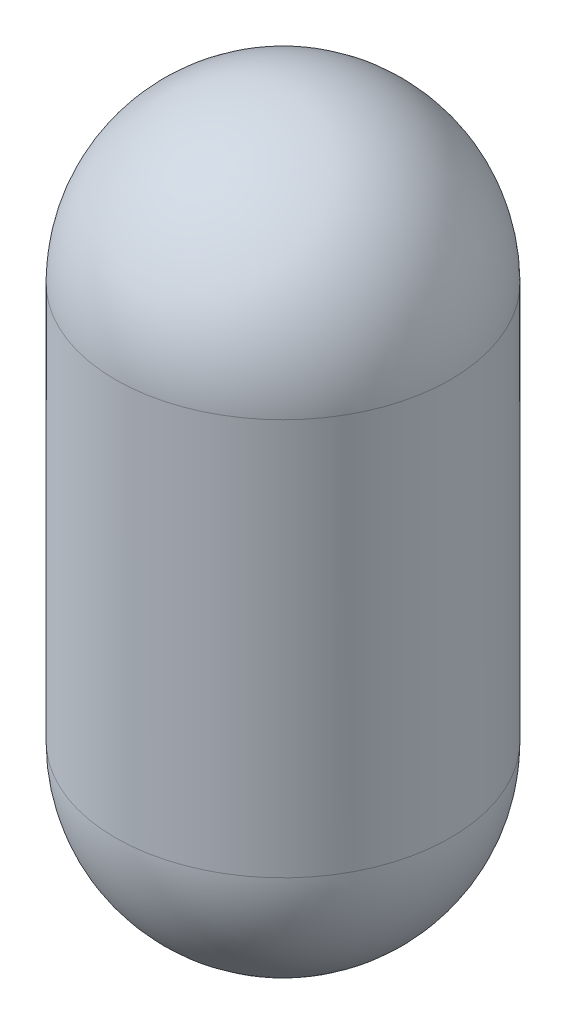
SolidWorks part; units mm, degrees
ref_plane "Front Plane" through (0, 0, 0) normal (0, 0, 1) x (1, 0, 0)
ref_plane "Top Plane" through (0, 0, 0) normal (0, 1, 0) x (1, 0, 0)
ref_plane "Right Plane" through (0, 0, 0) normal (1, 0, 0) x (0, 0, -1)
sketch "Sketch1" plane through (0, 0, 0) normal (0, 0, 1) x (1, 0, 0)
  line L0 (0, 87.9475) -> (0, -87.9475) construction
  line L2 (-74.295, 87.9475) -> (-74.295, -87.9475)
  line L3 (-71.12, 87.9475) -> (-71.12, -87.9475)
  line L5 (0, 162.2425) -> (0, 159.0675)
  line L6 (0, -162.2425) -> (0, -159.0675)
  line L7 (-74.295, -87.9475) -> (0, -87.9475) construction
  line L8 (74.2937, 88.3837) -> (74.295, -87.947) construction
  line L9 (71.1187, 88.3743) -> (71.12, -87.947) construction
  line L10 (-74.295, 87.9475) -> (0, 87.9475) construction
  line L11 (0, 159.0675) -> (0, 87.9475) construction
  line L12 (0, -159.0675) -> (0, -87.9475) construction
  arc A0 (0, 162.2425) -> (-74.295, 87.9475) centre (0, 87.9475) ccw
  arc A1 (-74.295, -87.9475) -> (0, -162.2425) centre (0, -87.9475) ccw
  arc A2 (0, 159.0675) -> (-71.12, 87.9475) centre (0, 87.9475) ccw
  arc A3 (-71.12, -87.9475) -> (0, -159.0675) centre (0, -87.9475) ccw
  arc A4 (-71.12, -87.9475) -> (71.12, -87.947) centre (0, -87.9475) ccw construction
  arc A5 (-74.295, -87.9475) -> (74.295, -87.947) centre (0, -87.9475) ccw construction
  arc A6 (74.2937, 88.3837) -> (-74.295, 87.9475) centre (0, 87.9475) ccw construction
  arc A7 (71.1187, 88.3743) -> (-71.12, 87.9475) centre (0, 87.9475) ccw construction
  point P0 (0, -166.6905)
  dimension "D1" = 175.895
  dimension "D2" = 74.295
  dimension "D3" = 3.175
revolve "Revolve3" add sketch "Sketch1" angle 360 about L0
